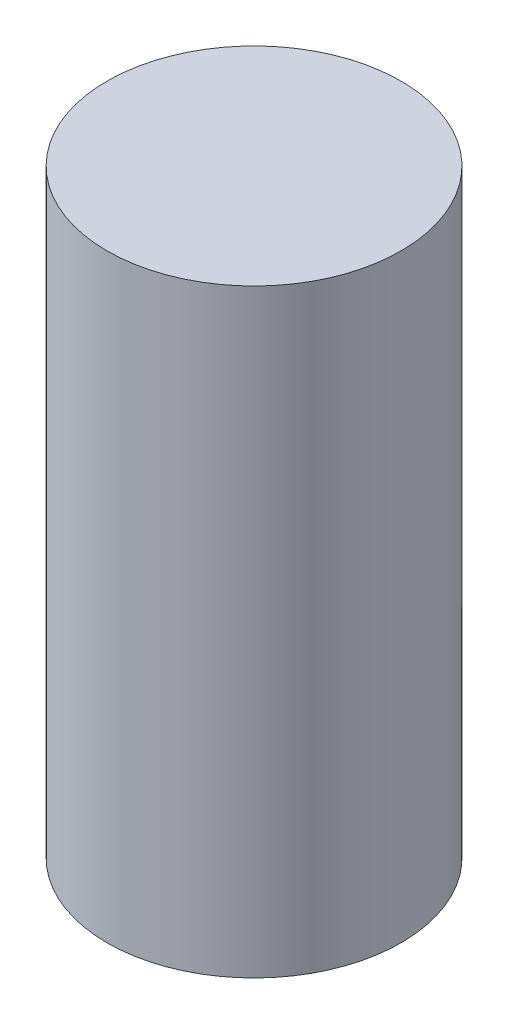
SolidWorks part; units mm, degrees
ref_plane "Plan de face" through (0, 0, 0) normal (0, 0, 1) x (1, 0, 0)
ref_plane "Plan de dessus" through (0, 0, 0) normal (0, 1, 0) x (1, 0, 0)
ref_plane "Plan de droite" through (0, 0, 0) normal (1, 0, 0) x (0, 0, -1)
sketch "Esquisse1" plane through (0, 0, 0) normal (0, 1, 0) x (1, 0, 0)
  circle A0 centre (0, 0) radius 73.61
  dimension "D1" = 147.22
extrude "Boss.-Extru.1" add sketch "Esquisse1" along normal blind 300
